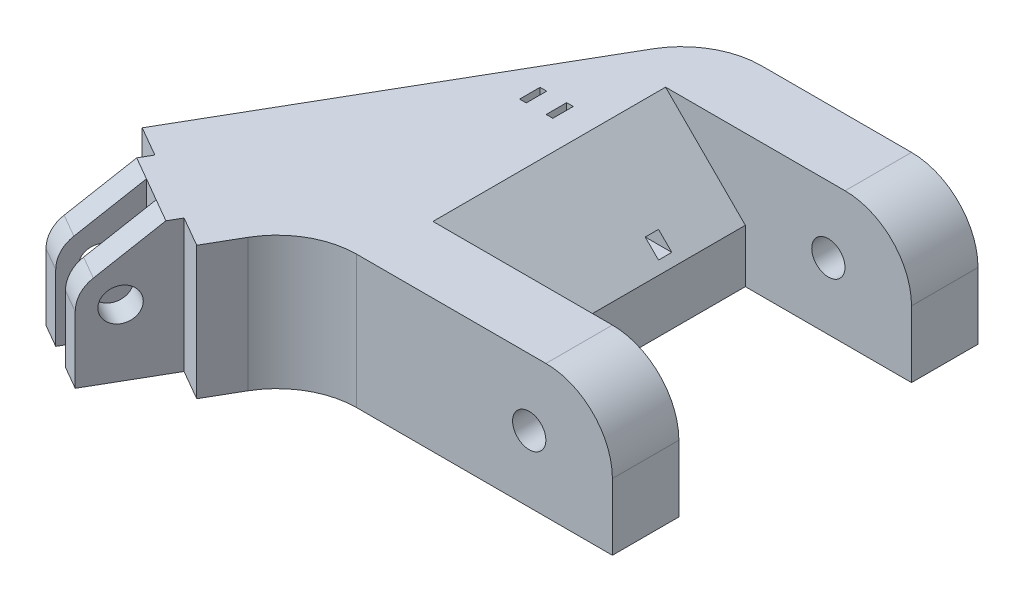
SolidWorks part; units mm, degrees
ref_plane "Front Plane" through (0, 0, 0) normal (0, 0, 1) x (1, 0, 0)
ref_plane "Top Plane" through (0, 0, 0) normal (0, 1, 0) x (1, 0, 0)
ref_plane "Right Plane" through (0, 0, 0) normal (1, 0, 0) x (0, 0, -1)
sketch "Sketch2" plane through (0, 0, 0) normal (0, 1, 0) x (1, 0, 0)
  line L0 (-0.9367, 51.2243) -> (-50.5408, -34.6926)
  line L1 (-0.9367, 51.2243) -> (41.6083, 51.2243)
  line L4 (41.6083, 51.2243) -> (41.6083, 38.5243)
  line L9 (-50.5408, -34.6926) -> (-46.1414, -37.2326)
  line L14 (-46.1414, -37.2326) -> (-39.7981, -26.2457)
  line L15 (-39.7981, -26.2457) -> (-35.3987, -28.7857)
  line L16 (-35.3987, -28.7857) -> (-41.742, -39.7726)
  line L17 (-41.742, -39.7726) -> (-37.3426, -42.3126)
  line L18 (-37.3426, -42.3126) -> (-30.9993, -31.3257)
  line L19 (-30.9993, -31.3257) -> (41.6083, -31.3257)
  line L20 (41.6083, -5.9257) -> (41.6083, -31.3257)
  line L21 (41.6083, -5.9257) -> (9.8583, -5.9257)
  line L23 (41.6083, 38.5243) -> (9.8583, 38.5243)
  line L24 (9.8583, -5.9257) -> (9.8583, 38.5243)
  dimension "D1" = 5.08
  dimension "D2" = 82.55
  dimension "D3" = 42.545
  dimension "D4" = 25.4
  dimension "D5" = 5.08
  dimension "D6" = 5.08
  dimension "D7" = 12.7
  dimension "D8" = 31.75
extrude "Boss-Extrude1" add sketch "Sketch2" along normal blind 25.4
sketch "Sketch8" plane through (0, 0, -51.2243) normal (0, 0, -1) x (-1, 0, 0)
  circle A0 centre (-25.7175, 12.7) radius 3.175
  dimension "D1" = 6.35
extrude "Cut-Extrude1" cut sketch "Sketch8" against normal through all and the other way through all
sketch "Sketch9" plane through (-9.6851, 0, -5.5917) normal (0.866, 0, 0.5) x (0.5, 0, -0.866)
  line L2 (-55.315, 0) -> (-42.6285, 0) construction
  line L3 (-55.315, 25.4) -> (-55.315, 0) construction
  circle A0 centre (-48.965, 12.7) radius 3.175
  dimension "D1" = 12.7
  dimension "D2" = 6.35
extrude "Cut-Extrude2" cut sketch "Sketch9" against normal blind 25.4
sketch "Sketch11" plane through (-9.6851, 0, -5.5917) normal (0.866, 0, 0.5) x (0.5, 0, -0.866)
  line L0 (-55.315, 25.4) -> (-55.315, 0) construction
  line L1 (-42.6285, 25.4) -> (-52.7783, 17.7776)
  line L2 (-55.315, 12.7) -> (-55.315, 25.4)
  line L3 (-55.315, 25.4) -> (-42.6285, 25.4)
  arc A0 (-55.315, 12.7) -> (-52.7783, 17.7776) centre (-48.965, 12.7) cw
extrude "Cut-Extrude3" cut sketch "Sketch11" against normal through all
sketch "Sketch12" plane through (0, 25.4, 0) normal (0, 1, 0) x (1, 0, 0)
  line L1 (41.6083, -31.3257) -> (41.6083, -5.9257) construction
  line L2 (41.6083, -18.6257) -> (-23.667, -18.6257)
  line L3 (-23.667, -18.6257) -> (-30.9993, -31.3257)
  line L4 (-30.9993, -31.3257) -> (41.6083, -31.3257)
  line L5 (41.6083, -31.3257) -> (41.6083, -18.6257)
extrude "Cut-Extrude4" cut sketch "Sketch12" against normal blind 25.4
sketch "Sketch14" plane through (-9.6851, 0, -5.5917) normal (0.866, 0, 0.5) x (0.5, 0, -0.866)
  line L0 (-27.9638, 25.4) -> (-42.6285, 25.4) construction
  line L1 (-40.0885, 25.4) -> (-6.6421, 25.4)
  line L2 (-40.0885, 25.4) -> (-40.0885, 0)
  line L3 (-40.0885, 0) -> (-6.6421, 0)
  line L4 (-6.6421, 25.4) -> (-6.6421, 0)
  dimension "D1" = 25.4
  dimension "D2" = 2.54
extrude "Boss-Extrude2" add sketch "Sketch14" along normal blind 6.604
sketch "Sketch15" plane through (-22.8833, 0, -13.2117) normal (-0.866, 0, -0.5) x (-0.5, 0, 0.866)
  line L0 (-43.8932, 25.4) -> (42.6285, 25.4) construction
  line L1 (40.0885, 25.4) -> (-43.8932, 25.4)
  line L2 (40.0885, 25.4) -> (40.0885, 0)
  line L3 (40.0885, 0) -> (-43.8932, 0)
  line L4 (-43.8932, 25.4) -> (-43.8932, 0)
  dimension "D1" = 2.54
extrude "Boss-Extrude3" add sketch "Sketch15" along normal blind 6.604
sketch "Sketch16" plane through (0, 25.4, 0) normal (0, 1, 0) x (1, 0, 0)
  line L0 (-0.9367, 51.2243) -> (-8.5623, 51.2243)
  line L1 (-48.6468, -18.204) -> (-6.6559, 54.5263) construction
  line L2 (-8.5623, 51.2243) -> (-6.6559, 54.5263)
  line L3 (-6.6559, 54.5263) -> (-0.9367, 51.2243) construction
  line L4 (-6.6559, 54.5263) -> (-0.9367, 51.2243)
extrude "Cut-Extrude5" cut sketch "Sketch16" against normal through all
fillet "Fillet11" radius 12.7 2 edges at (41.6083, 25.4, -44.8743) (41.6083, 25.4, 12.2757)
chamfer "Chamfer1" distance 15.24 angle 45 1 edges at (9.8583, 25.4, -16.2993)
fillet "Fillet12" radius 15.24 2 edges at (-8.5623, 12.7, -51.2243) (-16.0413, 12.7, 18.6257)
ref_plane "Plane1" through (0, 12.7, 0) normal (0, 1, 0) x (1, 0, 0)
sketch "Sketch19" plane through (0, 12.7, 0) normal (0, 1, 0) x (1, 0, 0)
  line L0 (-39.7981, -26.2457) -> (-35.3987, -28.7857)
  line L1 (-35.3987, -28.7857) -> (-5.3817, 23.2054)
  line L2 (-5.3817, -5.9257) -> (-5.3817, 38.5243) construction
  line L3 (-5.3817, 23.2054) -> (9.8583, 23.2054)
  line L4 (9.8583, 38.5243) -> (9.8583, -5.9257) construction
  line L5 (-39.7981, -26.2457) -> (-7.0631, 23.2054)
  line L6 (-5.3817, 25.7454) -> (9.8583, 25.7454)
  line L7 (9.8583, 25.7454) -> (9.8583, 23.2054)
  line L9 (-5.3817, 25.7454) -> (-17.281, 25.7454)
  line L11 (-7.0631, 23.2054) -> (-17.281, 23.2054)
  line L12 (-17.281, 25.7454) -> (-17.281, 23.2054)
  dimension "D1" = 2.54
extrude "Cut-Extrude6" cut sketch "Sketch19" against normal blind 1.27 and the other way blind 1.27
sketch "Sketch21" plane through (0, 25.4, 0) normal (0, 1, 0) x (1, 0, 0)
  line L1 (-17.3436, 26.5031) -> (-16.0736, 26.5031)
  line L2 (-17.3436, 26.5031) -> (-17.3436, 22.5941)
  line L3 (-17.3436, 22.5941) -> (-16.0736, 22.5941)
  line L4 (-16.0736, 26.5031) -> (-16.0736, 22.5941)
  line L5 (-12.2636, 26.5031) -> (-10.9936, 26.5031)
  line L6 (-12.2636, 26.5031) -> (-12.2636, 22.5941)
  line L7 (-12.2636, 22.5941) -> (-10.9936, 22.5941)
  line L8 (-10.9936, 26.5031) -> (-10.9936, 22.5941)
  dimension "D1" = 1.27
  dimension "D2" = 1.27
  dimension "D3" = 3.81
extrude "Cut-Extrude7" cut sketch "Sketch21" against normal through all both and the other way through all
